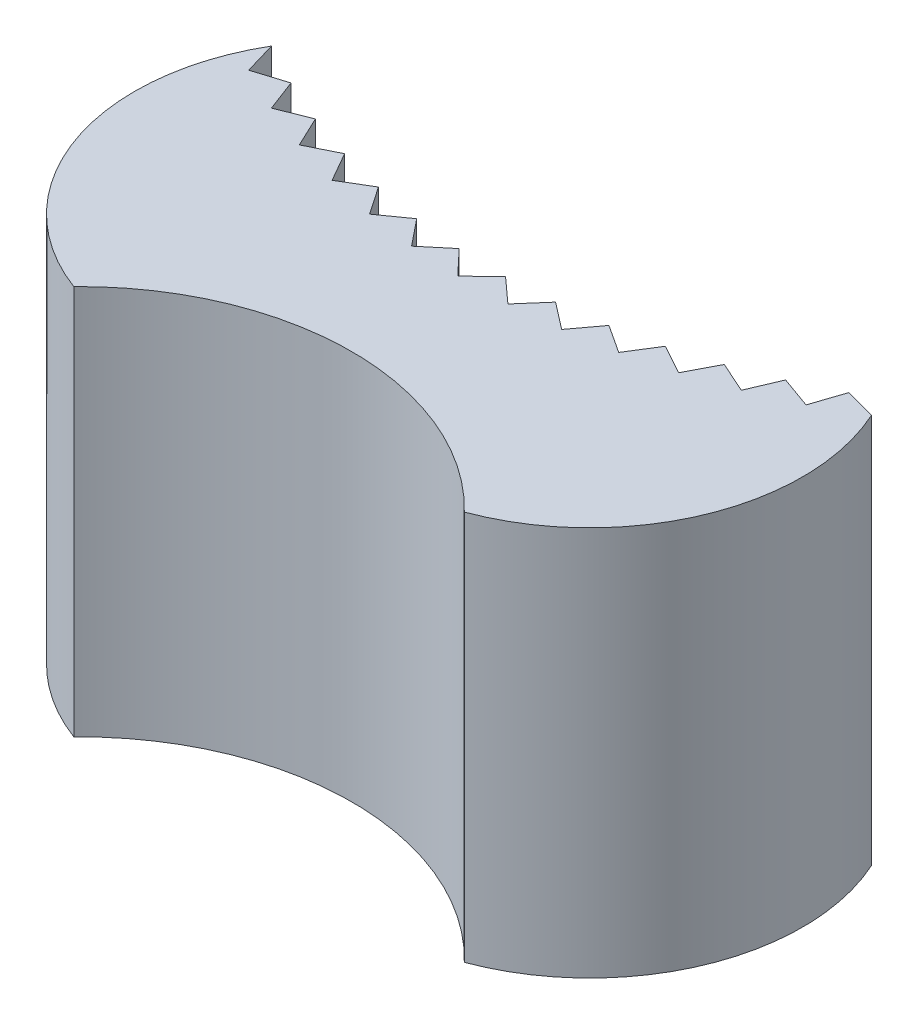
SolidWorks part; units mm, degrees
material "AISI Type A2 Tool Steel"
ref_plane "Front" through (0, 0, 0) normal (0, 0, 1) x (1, 0, 0)
ref_plane "Top" through (0, 0, 0) normal (0, 1, 0) x (1, 0, 0)
ref_plane "Right" through (0, 0, 0) normal (1, 0, 0) x (0, 0, -1)
sketch "Sketch1" plane through (0, 0, 0) normal (0, 1, 0) x (1, 0, 0)
  line L0 (0, 0.762) -> (0, -0.762) construction
  line L1 (0, -1.651) -> (0, 1.651) construction
  line L2 (3.275, 1.651) -> (-3.275, 1.651) construction
  line L3 (2.0984, -1.651) -> (-2.0984, -1.651) construction
  arc A0 (-3.275, 1.651) -> (3.275, 1.651) centre (0, 7.239) ccw
  arc A1 (2.0984, -1.651) -> (-2.0984, -1.651) centre (0, -3.683) ccw
  arc A2 (-3.275, 1.651) -> (-2.0984, -1.651) centre (-1.3007, 0.4939) ccw
  arc A4 (3.275, 1.651) -> (2.0984, -1.651) centre (1.3007, 0.4939) cw
  point P8 (0, 0)
  point P12 (0, 0)
  point P14 (0, 1.651)
  point P17 (0, -1.651)
  dimension "D1" = 12.954
  dimension "D2" = 5.842
  dimension "D4" = 3.302
  dimension "D5" = 2.2884
  dimension "D3" = 1.524
extrude "Boss-Extrude1" add sketch "Sketch1" along normal blind 4.191
sketch "Sketch2" plane through (0, 4.191, 0) normal (0, 1, 0) x (1, 0, 0)
  line L0 (-3.275, 1.651) -> (-3.1731, 1.3029)
  line L1 (-2.827, 1.4115) -> (-3.1731, 1.3029)
  line L2 (-3.1731, 1.3029) -> (-3.0534, 1.5269) construction
  arc A0 (-3.275, 1.651) -> (-2.827, 1.4115) centre (0, 7.239) ccw
  arc A1 (-3.275, 1.651) -> (3.275, 1.651) centre (0, 7.239) ccw construction
  point P34 (0, 0)
  dimension "D1" = 0.254
  dimension "D2" = 0.508
extrude "Cut-Extrude1" cut sketch "Sketch2" against normal blind 4.191
pattern_circular "CirPattern1" count 15 every 4.5 about axis through (0, 0, -7.239) along (0, 1, 0) of "Cut-Extrude1"
